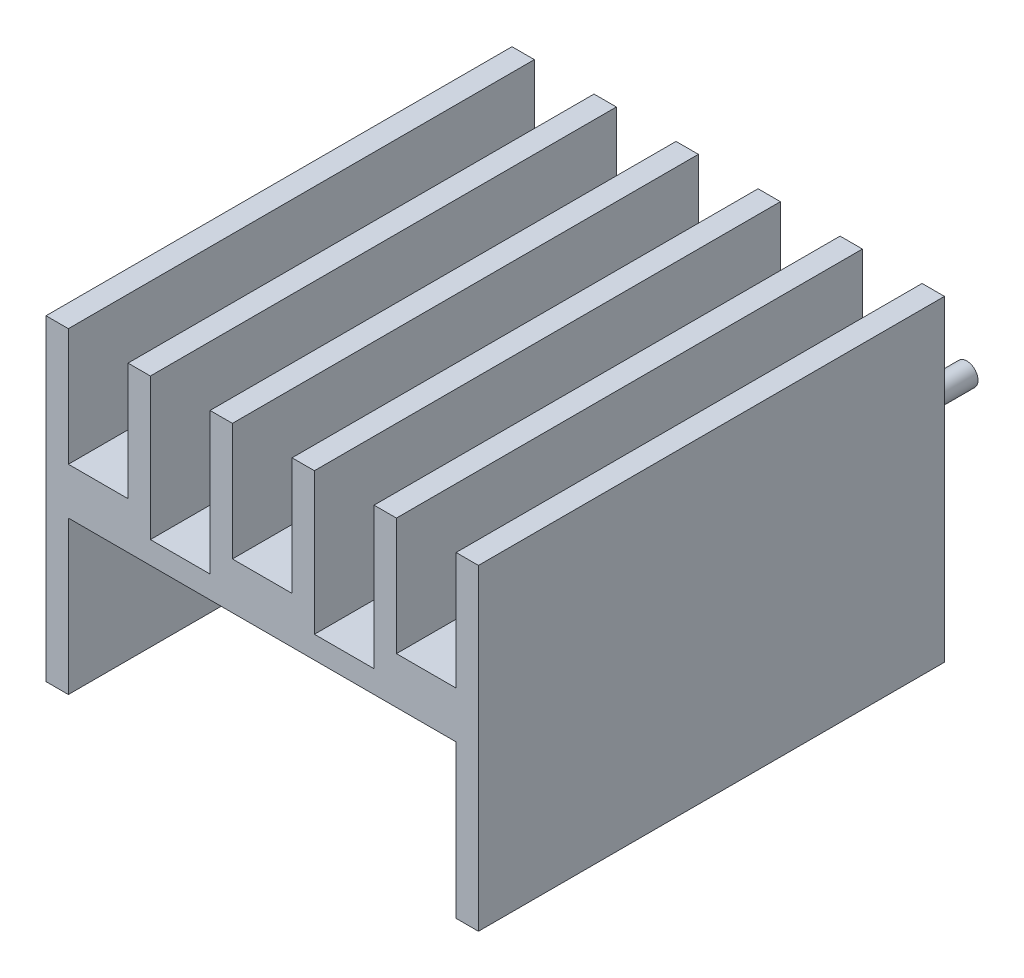
SolidWorks part; units mm, degrees
ref_plane "前视基准面" through (0, 0, 0) normal (0, 0, 1) x (1, 0, 0)
ref_plane "上视基准面" through (0, 0, 0) normal (0, 1, 0) x (1, 0, 0)
ref_plane "右视基准面" through (0, 0, 0) normal (1, 0, 0) x (0, 0, -1)
sketch "草图1" plane through (0, 0, 0) normal (0, 0, 1) x (1, 0, 0)
  line L0 (-26.1803, 0) -> (22.5692, 0) construction
  line L1 (0, 11.1634) -> (0, -11.6194) construction
  line L2 (-11.6, 8.8) -> (-11.6, -8.2)
  line L3 (-11.6, -8.2) -> (-10.4, -8.2)
  line L4 (-10.4, -8.2) -> (-10.4, 0)
  line L5 (-10.4, 0) -> (10.4, 0)
  line L7 (1.6, 2.5) -> (-1.6, 2.5)
  line L8 (-1.6, 2.5) -> (-1.6, 8.8)
  line L9 (-1.6, 8.8) -> (-2.8, 8.8)
  line L10 (-2.8, 8.8) -> (-2.8, 1.2)
  line L11 (-2.8, 1.2) -> (-6, 1.2)
  line L12 (-6, 1.2) -> (-6, 8.8)
  line L13 (-6, 8.8) -> (-7.2, 8.8)
  line L14 (-7.2, 8.8) -> (-7.2, 2.5)
  line L15 (-7.2, 2.5) -> (-10.4, 2.5)
  line L16 (-10.4, 2.5) -> (-10.4, 8.8)
  line L17 (-10.4, 8.8) -> (-11.6, 8.8)
  line L18 (10.4, 8.8) -> (11.6, 8.8)
  line L19 (10.4, 2.5) -> (10.4, 8.8)
  line L20 (7.2, 2.5) -> (10.4, 2.5)
  line L21 (7.2, 8.8) -> (7.2, 2.5)
  line L22 (6, 8.8) -> (7.2, 8.8)
  line L23 (6, 1.2) -> (6, 8.8)
  line L24 (2.8, 1.2) -> (6, 1.2)
  line L25 (2.8, 8.8) -> (2.8, 1.2)
  line L26 (1.6, 8.8) -> (2.8, 8.8)
  line L27 (1.6, 2.5) -> (1.6, 8.8)
  line L28 (10.4, -8.2) -> (10.4, 0)
  line L29 (11.6, -8.2) -> (10.4, -8.2)
  line L30 (11.6, 8.8) -> (11.6, -8.2)
  dimension "D1" = 11.6
  dimension "D2" = 1.2
  dimension "D3" = 8.8
  dimension "D4" = 17
  dimension "D5" = 1.2
  dimension "D6" = 2.5
  dimension "D7" = 1.2
  dimension "D8" = 1.2
  dimension "D9" = 3.2
  dimension "D10" = 3.2
extrude "凸台-拉伸1" add sketch "草图1" along normal blind 25
sketch "草图2" plane through (0, 0, 0) normal (0, 0, -1) x (-1, 0, 0)
  line L0 (0, -9.9137) -> (0, 13.601) construction
  line L1 (-8.8, -1.1613) -> (-8.8, 5.164) construction
  line L2 (-7.2, 2.5) -> (-7.2, 8.8) construction
  line L3 (-10.4, 8.8) -> (-10.4, 2.5) construction
  line L4 (-10.3941, 1.8) -> (-7.4623, 1.8) construction
  line L5 (-6, 1.2) -> (-2.8, 1.2) construction
  line L6 (10.3941, 1.8) -> (7.4623, 1.8) construction
  line L7 (8.8, -1.1613) -> (8.8, 5.164) construction
  circle A0 centre (-8.8, 1.8) radius 0.6
  circle A1 centre (8.8, 1.8) radius 0.6
  dimension "D1" = 1.2
  dimension "D2" = 0.6
extrude "凸台-拉伸2" add sketch "草图2" along normal blind 4
